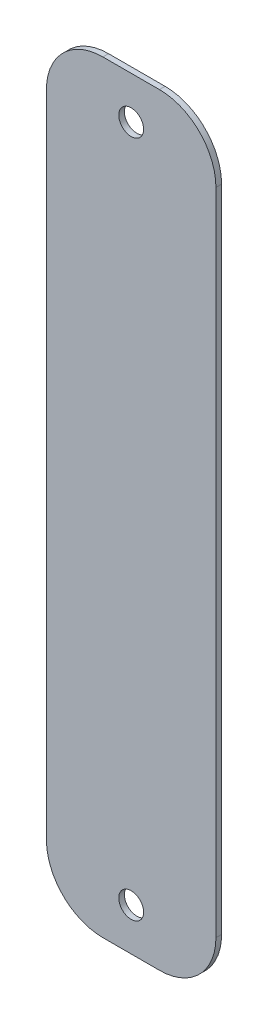
SolidWorks part; units mm, degrees
material "AISI 304"
ref_plane "Спереди" through (0, 0, 0) normal (0, 0, 1) x (1, 0, 0)
ref_plane "Сверху" through (0, 0, 0) normal (0, 1, 0) x (1, 0, 0)
ref_plane "Справа" through (0, 0, 0) normal (1, 0, 0) x (0, 0, -1)
other "Configuration Table"
sketch "Эскиз1" plane through (0, 0, 0) normal (0, 0, 1) x (1, 0, 0)
  line L0 (50, 0) -> (-50, 0) construction
  line L1 (-30, -135) -> (30, -135)
  line L2 (-30, -135) -> (-30, 135)
  line L3 (-30, 135) -> (30, 135)
  line L4 (30, -135) -> (30, 135)
  line L5 (0, 135) -> (0, -135) construction
  line L6 (-30, 0) -> (30, 0) construction
  circle A0 centre (0, 120) radius 4.4
  circle A1 centre (0, -120) radius 4.4
  point P0 (0, 0)
  dimension "D3" = 8.8
  dimension "D4" = 15
  dimension "D1" = 60
  dimension "D2" = 270
extrude "Бобышка-Вытянуть1" add sketch "Эскиз1" along normal blind 2
fillet "Скругление1" radius 20 4 edges at (30, -135, 1) (-30, -135, 1) (-30, 135, 1) (30, 135, 1)
move or copy body "Тело-Переместить/Копировать2" [suppressed] bodies to move or copy 103 parameters "D1"=0, "D2"=0, "D3"=0
move or copy body "Тело-Переместить/Копировать1" [suppressed] bodies to move or copy 103 parameters "D1"=0, "D2"=0, "D3"=0
